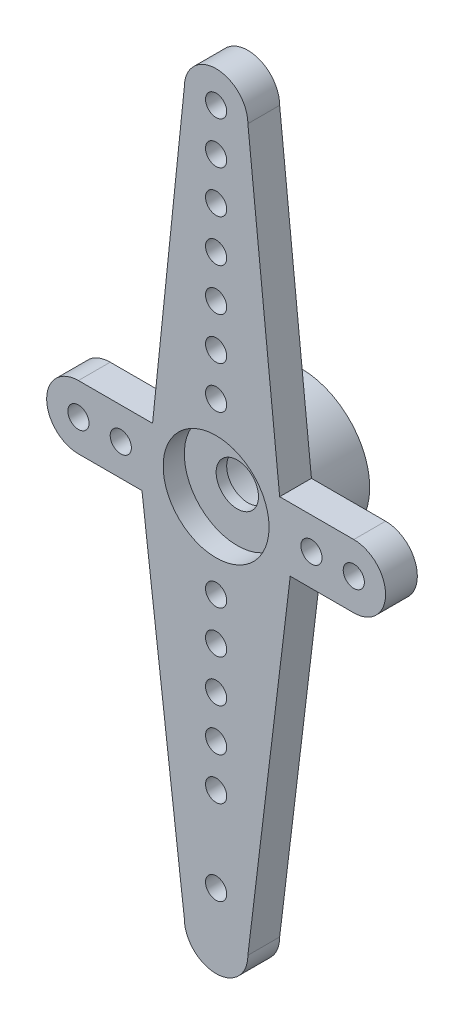
SolidWorks part; units mm, degrees
ref_plane "前视基准面" through (0, 0, 0) normal (0, 0, 1) x (1, 0, 0)
ref_plane "上视基准面" through (0, 0, 0) normal (0, 1, 0) x (1, 0, 0)
ref_plane "右视基准面" through (0, 0, 0) normal (1, 0, 0) x (0, 0, -1)
sketch "草图1" plane through (0, 0, 0) normal (0, 0, 1) x (1, 0, 0)
  line L0 (0, 4.5547) -> (0, -4.399) construction
  line L1 (1.5, 16) -> (3, 1.5)
  line L2 (3, 1.5) -> (6.5, 1.5)
  line L3 (6.5, -1.5) -> (3.5, -1.5)
  line L4 (3.5, -1.5) -> (1.5, -18)
  line L5 (-3.5, -1.5) -> (-1.5, -18)
  line L6 (-6.5, -1.5) -> (-3.5, -1.5)
  line L7 (-3, 1.5) -> (-6.5, 1.5)
  line L8 (-1.5, 16) -> (-3, 1.5)
  line L9 (-1.9534, 0) -> (2.2638, 0) construction
  arc A0 (1.5, 16) -> (-1.5, 16) centre (0, 16) ccw
  arc A1 (-1.5, -18) -> (1.5, -18) centre (0, -18) ccw
  arc A2 (6.5, -1.5) -> (6.5, 1.5) centre (6.5, 0) ccw
  arc A3 (-6.5, -1.5) -> (-6.5, 1.5) centre (-6.5, 0) cw
  circle A4 centre (-6.5, 0) radius 0.5
  circle A5 centre (0, 0) radius 1
  circle A6 centre (-4.5, 0) radius 0.5
  circle A7 centre (4.5, 0) radius 0.5
  circle A8 centre (6.5, 0) radius 0.5
  circle A9 centre (0, 16) radius 0.5
  circle A10 centre (0, 14) radius 0.5
  circle A11 centre (0, 12) radius 0.5
  circle A12 centre (0, 10) radius 0.5
  circle A13 centre (0, 8) radius 0.5
  circle A14 centre (0, 6) radius 0.5
  circle A15 centre (0, 4) radius 0.5
  circle A16 centre (0, -16) radius 0.5
  circle A17 centre (0, -4) radius 0.5
  circle A18 centre (0, -6) radius 0.5
  circle A19 centre (0, -8) radius 0.5
  circle A20 centre (0, -10) radius 0.5
  circle A21 centre (0, -12) radius 0.5
  dimension "D4" = 3
  dimension "D5" = 3
  dimension "D6" = 3
  dimension "D9" = 1
  dimension "D10" = 2
  dimension "D11" = 1
  dimension "D13" = 1
  dimension "D1" = 16
  dimension "D2" = 18
  dimension "D3" = 6.5
  dimension "D7" = 3.5
  dimension "D8" = 3
  dimension "D12" = 2
  dimension "D14" = 7
extrude "凸台-拉伸1" add sketch "草图1" along normal blind 1.5
sketch "草图2" plane through (0, 0, 0) normal (0, 0, -1) x (-1, 0, 0)
  circle A0 centre (0, 0) radius 3.25
  circle A1 centre (0, 0) radius 2
  dimension "D1" = 6.5
  dimension "D2" = 4
extrude "凸台-拉伸2" add sketch "草图2" along normal blind 2.5
sketch "草图3" plane through (0, 0, 1.5) normal (0, 0, 1) x (1, 0, 0)
  circle A0 centre (0, 0) radius 2.5
  dimension "D1" = 5
extrude "切除-拉伸1" cut sketch "草图3" against normal blind 1
